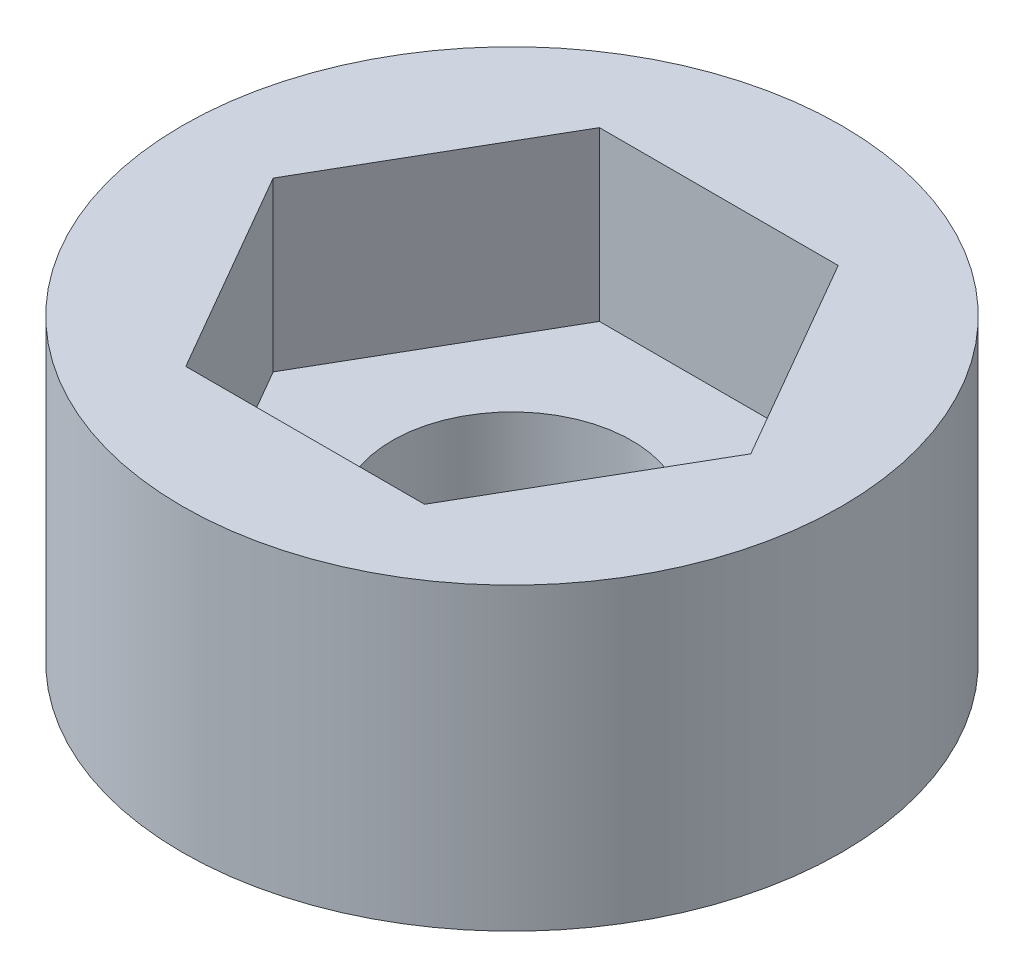
SolidWorks part; units mm, degrees
ref_plane "Front Plane" through (0, 0, 0) normal (0, 0, 1) x (1, 0, 0)
ref_plane "Top Plane" through (0, 0, 0) normal (0, 1, 0) x (1, 0, 0)
ref_plane "Right Plane" through (0, 0, 0) normal (1, 0, 0) x (0, 0, -1)
sketch "Sketch1" plane through (0, 0, 0) normal (0, 1, 0) x (1, 0, 0)
  circle A0 centre (0, 0) radius 11
  circle A1 centre (0, 0) radius 4
  dimension "D1" = 22
  dimension "D2" = 8
extrude "Boss-Extrude1" add sketch "Sketch1" along normal blind 10
sketch "Sketch2" plane through (0, 10, 0) normal (0, 1, 0) x (1, 0, 0)
  line L0 (-21.6435, 0) -> (19.7802, 0) construction
  line L1 (3.9837, 6.9) -> (-3.9837, 6.9)
  line L2 (-3.9837, 6.9) -> (-7.9674, 0)
  line L3 (-7.9674, 0) -> (-3.9837, -6.9)
  line L4 (-3.9837, -6.9) -> (3.9837, -6.9)
  line L5 (3.9837, -6.9) -> (7.9674, 0)
  line L6 (7.9674, 0) -> (3.9837, 6.9)
  circle A0 centre (0, 0) radius 6.9 construction
  dimension "D1" = 13.8
extrude "Cut-Extrude1" cut sketch "Sketch2" against normal blind 5.6
sketch "Sketch3" plane through (0, 0, 0) normal (1, 0, 0) x (0, 0, -1)
  line L0 (11, 10) -> (-11, 10) construction
  circle A0 centre (0, 21) radius 11
  arc A1 (11, 10) -> (-11, 10) centre (0, 21) ccw
  dimension "D1" = 22
